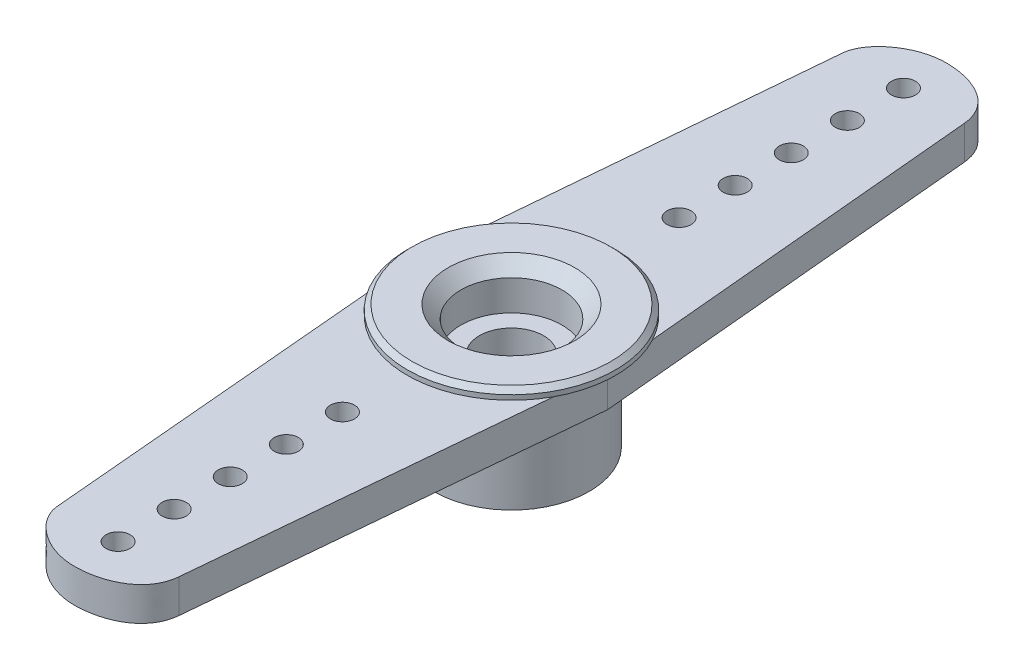
SolidWorks part; units mm, degrees
ref_plane "Front Plane" through (0, 0, 0) normal (0, 0, 1) x (1, 0, 0)
ref_plane "Top Plane" through (0, 0, 0) normal (0, 1, 0) x (1, 0, 0)
ref_plane "Right Plane" through (0, 0, 0) normal (1, 0, 0) x (0, 0, -1)
sketch "Sketch1" plane through (0, 0, 0) normal (0, 1, 0) x (1, 0, 0)
  circle A0 centre (0, 0) radius 4.85
  dimension "D1" = 9.7
extrude "Base" add sketch "Sketch1" along normal blind 5
sketch "Sketch2" plane through (0, 5, 0) normal (0, 1, 0) x (1, 0, 0)
  line L0 (0, 0) -> (-0.0621, 33.7183) construction
  line L1 (-11.9725, 0) -> (11.947, 0) construction
  line L2 (-8.3219, 24.5) -> (6.6435, 24.5) construction
  line L3 (6, 0) -> (3.7549, 24.5)
  line L4 (-6, -0.0221) -> (-3.8451, 24.486)
  line L5 (-3.7477, 25.5942) -> (-3.9438, 23.3636) construction
  line L6 (3.8863, 23.0658) -> (3.6222, 25.9485) construction
  line L7 (1.4275, 27.2) -> (-1.5326, 27.2) construction
  line L8 (6, 0) -> (3.7549, -24.5)
  line L9 (-6, 0.0221) -> (-3.8451, -24.486)
  circle A0 centre (0, 0) radius 6 construction
  circle A1 centre (-0.0451, 24.5) radius 0.75
  circle A2 centre (-0.0451, 21) radius 0.75
  circle A3 centre (-0.0451, 17.5) radius 0.75
  circle A4 centre (-0.0451, 14) radius 0.75
  circle A5 centre (-0.0451, 10.5) radius 0.75
  circle A6 centre (-0.0451, -10.5) radius 0.75
  circle A7 centre (-0.0451, -14) radius 0.75
  circle A8 centre (-0.0451, -17.5) radius 0.75
  circle A9 centre (-0.0451, -21) radius 0.75
  circle A10 centre (-0.0451, -24.5) radius 0.75
  circle A11 centre (0, 0) radius 3.15
  spline S0 degree 3 poles (-3.8451, 24.486) (-3.7348, 25.7407) (-1.8986, 27.2296) (1.7986, 27.1915) (3.6063, 26.1215) (3.7549, 24.5) knots 0 0 0 0 0.45 0.55 1 1 1 1
  spline S1 degree 3 poles (-3.8451, -24.486) (-3.7348, -25.7407) (-1.8986, -27.2296) (1.7986, -27.1915) (3.6063, -26.1215) (3.7549, -24.5) knots 0 0 0 0 0.45 0.55 1 1 1 1
  circle M2 centre (0, 0) radius 4.85
  dimension "D1" = 12
  dimension "D4" = 1.5
  dimension "D6" = 5
  dimension "D7" = 6.3
  dimension "D2" = 24.5
  dimension "D3" = 7.6
  dimension "D5" = 27.2
extrude "Boss-Extrude2" add sketch "Sketch2" along normal blind 2.1 separate body contours A11 M2 | L9 S1 L8 L3 S0 L4 A10 A8 A6 A5 A4 A3 A2 A1 A7 A9 M2
sketch "Sketch3" plane through (0, 7.1, 0) normal (0, 1, 0) x (1, 0, 0)
  circle A0 centre (0, 0) radius 6.5
  circle A1 centre (0, 0) radius 3.15 construction
  circle A2 centre (0, 0) radius 3.15
  dimension "D1" = 13
extrude "Boss-Extrude3" add sketch "Sketch3" along normal blind 0.6
chamfer "Chamfer1" distance 0.8 angle 45 1 edges at (0, 7.7, 3.15)
chamfer "Chamfer2" distance 0.3 angle 45 1 edges at (0, 7.7, 6.5)
sketch "Sketch4" plane through (0, 0, 0) normal (0, -1, 0) x (1, 0, 0)
  line L0 (0, 0) -> (0, -4.12) construction
  line L1 (-0.2627, -2.6369) -> (0, -2.95)
  line L2 (0.2627, -2.6369) -> (0, -2.95)
  arc A0 (-0.2627, -2.6369) -> (0.2627, -2.6369) centre (0, 0) ccw
  point P7 (0, -2.65)
  dimension "D1" = 5.3
  dimension "D2" = 80
  dimension "D3" = 0.3
extrude "Cut-Extrude1" cut sketch "Sketch4" against normal blind 3
pattern_circular "CirPattern1" count 26 over 360 about axis through (0, 0, 0) along (0, 1, 0) of "Cut-Extrude1"
sketch "Sketch5" plane through (0, 0, 0) normal (0, -1, 0) x (1, 0, 0)
  circle A0 centre (0, 0) radius 2.65
extrude "Cut-Extrude2" cut sketch "Sketch5" against normal blind 3
sketch "Sketch6" plane through (0, 3, 0) normal (0, -1, 0) x (1, 0, 0)
  circle A0 centre (0, 0) radius 2
  dimension "D1" = 4
extrude "Cut-Extrude3" cut sketch "Sketch6" against normal blind 3
